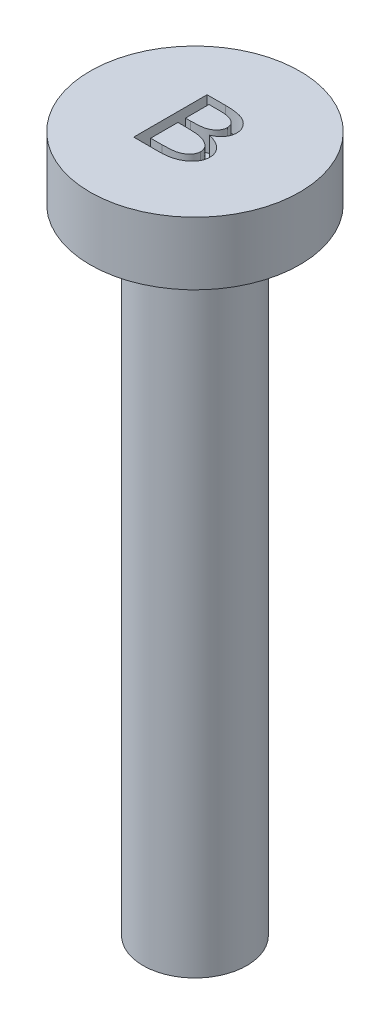
SolidWorks part; units mm, degrees
ref_plane "Front Plane" through (0, 0, 0) normal (0, 0, 1) x (1, 0, 0)
ref_plane "Top Plane" through (0, 0, 0) normal (0, 1, 0) x (1, 0, 0)
ref_plane "Right Plane" through (0, 0, 0) normal (1, 0, 0) x (0, 0, -1)
sketch "Sketch1" plane through (0, 0, 0) normal (0, 1, 0) x (1, 0, 0)
  circle A0 centre (0, 0) radius 2.475
  dimension "D1" = 4.95
extrude "Boss-Extrude1" add sketch "Sketch1" along normal blind 30.2
sketch "Sketch2" plane through (0, 30.2, 0) normal (0, 1, 0) x (1, 0, 0)
  circle A0 centre (0, 0) radius 5
  dimension "D1" = 10
extrude "Boss-Extrude2" add sketch "Sketch2" along normal blind 3
sketch "Sketch4" plane through (0, 0, 0) normal (0, -1, 0) x (1, 0, 0)
  line L0 (0, 2.475) -> (0, -2.475) construction
  circle A0 centre (0, 0) radius 2.475 construction
sketch "Sketch8" plane through (0, 0, 0) normal (0, -1, 0) x (1, 0, 0)
  circle A0 centre (0, 0) radius 2.5
hole_wizard "M2.5x0.45 Tapped Hole2" positions "Sketch13" profile "Sketch14" tap size "M2.5x0.45" standard "BSI"
sketch "Sketch13" plane through (0, 0, 0) normal (0, -1, 0) x (-1, 0, 0)
  point P0 (0, 0)
sketch "Sketch14" plane through (0, 0, 0) normal (1, 0, 0) x (0, 0, -1)
  line L0 (0, 0) -> (0, 7.8659)
  line L1 (0, 7.8659) -> (1.025, 7.25)
  line L2 (1.025, 7.25) -> (1.025, 0)
  line L5 (1.025, 0) -> (0, 0)
  line L10 (0, 7.8659) -> (-1.025, 7.25) construction
  line L11 (0, -6.35) -> (0, 107.95) construction
  dimension "Tap Drill Dia." = 2.05
  dimension "Tap Drill Depth" = 7.25
  dimension "Drill Angle" = 118
cosmetic thread "Hole Thread2" parameters "D1"=5, "D2"=2.5
sketch "Sketch15" plane through (0, 33.2, 0) normal (0, 1, 0) x (1, 0, 0)
  line L0 (-4.7068, -1.687) -> (4.7068, -1.687) construction
  circle A0 centre (0, 0) radius 5 construction
  text T0 "B" font "Century Gothic" height 3.5
extrude "Cut-Extrude1" cut sketch "Sketch15" against normal blind 1
